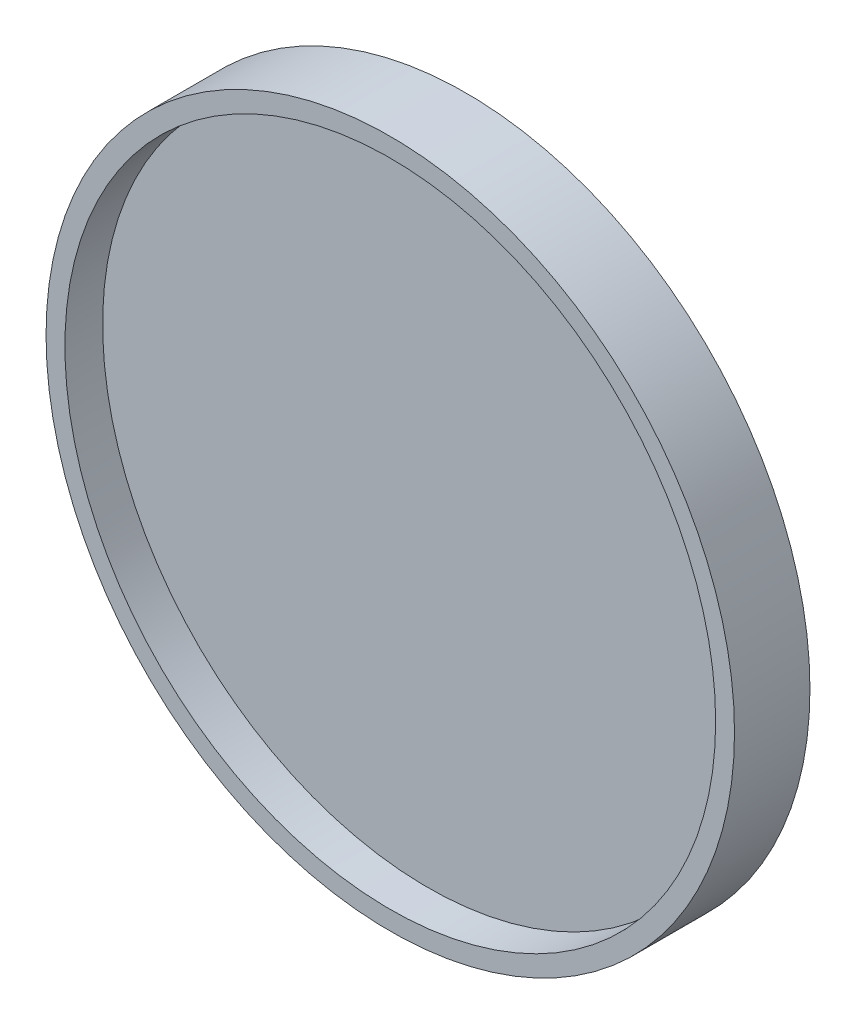
SolidWorks part; units mm, degrees
ref_plane "Front Plane" through (0, 0, 0) normal (0, 0, 1) x (1, 0, 0)
ref_plane "Top Plane" through (0, 0, 0) normal (0, 1, 0) x (1, 0, 0)
ref_plane "Right Plane" through (0, 0, 0) normal (1, 0, 0) x (0, 0, -1)
sketch "Sketch1" plane through (0, 0, 0) normal (0, 0, 1) x (1, 0, 0)
  circle A0 centre (0, 0) radius 43.815
  circle A1 centre (0, 0) radius 46.355
  dimension "D1" = 87.63
  dimension "D2" = 92.71
extrude "Boss-Extrude1" add sketch "Sketch1" along normal blind 5.08
sketch "Sketch2" plane through (0, 0, 0) normal (0, 0, -1) x (-1, 0, 0)
  circle A0 centre (0, 0) radius 46.355
extrude "Boss-Extrude2" add sketch "Sketch2" along normal blind 5.08
equation "\"FoamCore\" = \".2\""
equation "\"MDF\" = \".2\""
equation "\"GMaterial\"= \".2\""
equation "\"PVCMountDiameter\" = \"0.5in\""
equation "\"PVCMountDistanceToEdge\" = \"0.5\""
equation "\"PVCThickness\" = \"0.13in\""
equation "\"PVCDiameter\" = 1.5in"
equation "\"BaseWidth\" = \"8in\""
equation "\"BaseLength\" = \"10in\""
equation "\"BallDiameter\" = \"1.57in\""
equation "\"BaseGap\" = \"4in\""
equation "\"FunnelTopDiameter\" = \"8in\""
equation "\"FunnelTopDepth\" = \"0.5in\""
equation "\"BallGap\" = \"0.1in\""
equation "\"FunnelLength\" = 3in"
equation "\"FunnelMaterial\" = 0.1in"
equation "\"FunnelLowerDiameter\" = 1.9in"
equation "\"FunnelDepth\" = 1.5in"
equation "\"FunnelBendLength\" = 2*pi*\"FunnelLowerDiameter\"/2*135"
equation "\"AmmoFeederLength\" = 1.5in + 76mm"
equation "\"AmmoFeederCutoffLength\" = \"MovingWheelDiameter\""
equation "\"WheelThickness\" = 0.5in"
equation "\"LauncherWheelDiameter\" = 76mm"
equation "\"MotorFrontLength\" = 0.95in"
equation "\"MotorBodyTotalLength\" = 2.03in"
equation "\"MotorFrontDiameter\" = 1.5in"
equation "\"MotorLowerDriveshaftDiameter\" = 0.46in"
equation "\"MotorLowerDriveshaftThickness\" = 0.25in"
equation "\"MotorFullDriveshaftLength\" = 0.78in"
equation "\"MotorDriveshaftDiameter\" = 0.23in"
equation "\"MotorDriveshaftFlatThickness\" = 0.2in"
equation "\"MotorRearDiameter\" = 31.9mm"
equation "\"MotorDriveshaftBottomToTop\" = 31.1mm"
equation "\"MotorFlatDriveshaftLength\" = 11.7mm"
equation "\"MotorDistanceBetweenLowerandTopHoles\" = 0.5in"
equation "\"MotorMountsDistanceFromEdge\" = 0.06in"
equation "\"MotorScrewMountDiameter\" = 0.1in"
equation "\"MotorScrewMountDepth\" = 0.13in"
equation "\"HBRidgeScrewHoleDeep\" = 0.18in"
equation "\"MotorMountWidth\" = \"1.61in\""
equation "\"MotorMountLength\" = \"1.58in\""
equation "\"MotorMountToEdgeGap\" = \"3.3mm\""
equation "\"MotorMountToInsideEdgeGap\" = \"6.5mm\""
equation "\"MotorMountToMountWidthGap\" = \"25.8mm\""
equation "\"MotorMountToMountLengthGap\" = \"20.5mm\""
equation "\"MotorMountMaterialThickness\" = 1.6mm"
equation "\"MotorMountBaseScrewholeDiameter\" = 3.8mm"
equation "\"MotorMountBaseDistancebetweenHoles\" = 0.8in"
equation "\"MotorMountHeight\" = 1.85in"
equation "\"HBridgeWidth\" = 2.25in"
equation "\"HBridgeLength\" = 1.40in"
equation "\"UnoWidth\" = 3.13in"
equation "\"UnoLength\" = 3.06in"
equation "\"BatteryWidth\" = 1.15in"
equation "\"BatteryLength\" = 3.86in"
equation "\"ScrewDiameter\" = 2.7mm"
equation "\"MotorMountFaceScrewtoBase\" = 0.46in"
equation "\"MotorMountFaceDistanceBetweenScrews\" = 0.95in"
equation "\"MotorMountFaceMiddletoEdge\" = 0.16in"
equation "\"MotorMountFaceBottomtoEdge\" = 0.42in"
equation "\"MotorMountCenterholeHeight\" = 1.04in"
equation "\"MotorMountCenterholetoEdge\" = 0.25in"
equation "\"MovingWheelDiameter\" = 76mm"
equation "\"MovingWheelThickness\" = 0.5in"
equation "\"BraceLength\" = 1in"
equation "\"BraceVerticalOffset\" = 3.5in"
equation "\"BraceHorizontalOffset\" = 2.5in"
equation "\"BaseToBaseDistance\" = 7in"
equation "\"PVCOutsideDiameter\" = \"PVCDiameter\" + 2*\"PVCThickness\""
equation "\"Distancebetweenwalls\" = 6in"
equation "\"Slidewidth\" = 0.3in"
equation "\"Slidelength\" = 0.8in"
equation "\"Bottomtofloor\" = 0.53in"
equation "\"tabdistance\" = 0.2in"
equation "\"tabwidth\" = 0.3in"
equation "\"D2@Sketch1\"=3.45+\"MDF\""
equation "\"D1@Boss-Extrude1\"=\"MDF\""
equation "\"D1@Boss-Extrude2\"=\"MDF\""
